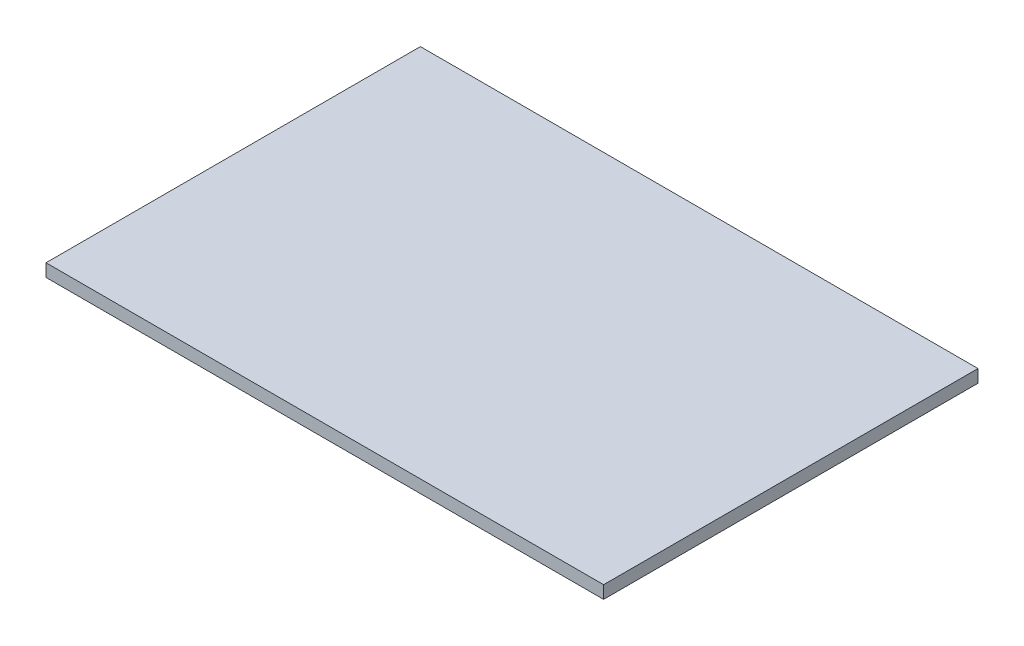
SolidWorks part; units mm, degrees
ref_plane "前视基准面" through (0, 0, 0) normal (0, 0, 1) x (1, 0, 0)
ref_plane "上视基准面" through (0, 0, 0) normal (0, 1, 0) x (1, 0, 0)
ref_plane "右视基准面" through (0, 0, 0) normal (1, 0, 0) x (0, 0, -1)
sketch "草图1" plane through (0, 0, 0) normal (0, 1, 0) x (1, 0, 0)
  line L1 (-35, 23.5) -> (35, 23.5)
  line L2 (-35, 23.5) -> (-35, -23.5)
  line L3 (-35, -23.5) -> (35, -23.5)
  line L4 (35, 23.5) -> (35, -23.5)
  line L5 (-35, 23.5) -> (35, -23.5) construction
  line L6 (-35, -23.5) -> (35, 23.5) construction
  point P0 (0, 0)
  dimension "D1" = 70
  dimension "D2" = 47
extrude "凸台-拉伸1" add sketch "草图1" along normal blind 1.6
sketch "草图2" plane through (0, 0, 0) normal (0, -1, 0) x (1, 0, 0)
  line L0 (-41.2308, 0) -> (45.8847, 0) construction
  line L1 (0, -26.6873) -> (0, 28.5053) construction
  circle A0 centre (-30.6868, -18.0339) radius 1.5
  circle A1 centre (28.2871, -18.0339) radius 1.5
  circle A2 centre (28.2871, 17.4522) radius 1.5
  circle A3 centre (-30.6868, 17.4522) radius 1.5
  dimension "D1" = 3
  dimension "D2" = 3
  dimension "D3" = 3
  dimension "D4" = 3
